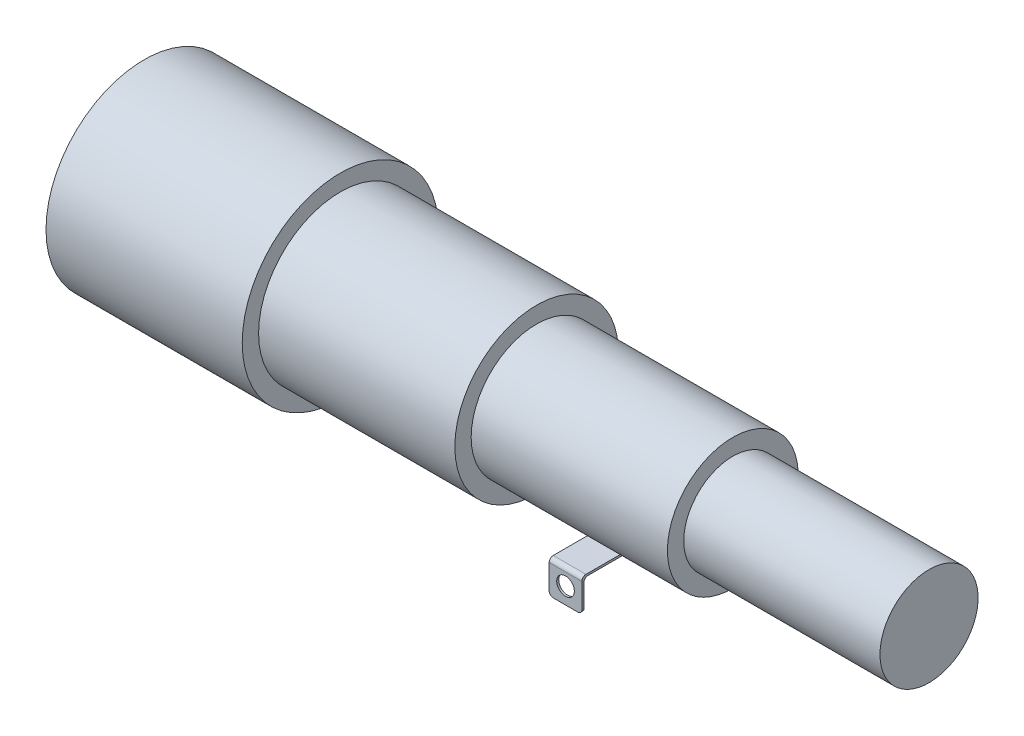
SolidWorks part; units mm, degrees
ref_plane "Front Plane" through (0, 0, 0) normal (0, 0, 1) x (1, 0, 0)
ref_plane "Top Plane" through (0, 0, 0) normal (0, 1, 0) x (1, 0, 0)
ref_plane "Right Plane" through (0, 0, 0) normal (1, 0, 0) x (0, 0, -1)
sketch "Sketch1" plane through (0, 0, 0) normal (1, 0, 0) x (0, 0, -1)
  circle A0 centre (0, 0) radius 152.4
  dimension "D1" = 304.8
extrude "Boss-Extrude1" add sketch "Sketch1" along normal blind 304.8 contours A0
sketch "Sketch2" plane through (304.8, 0, 0) normal (1, 0, 0) x (0, 0, -1)
  circle A0 centre (0, 0) radius 127
  dimension "D1" = 254
extrude "Boss-Extrude2" add sketch "Sketch2" along normal blind 304.8
sketch "Sketch3" plane through (609.6, 0, 0) normal (1, 0, 0) x (0, 0, -1)
  circle A0 centre (0, 0) radius 101.6
  dimension "D1" = 203.2
extrude "Boss-Extrude3" add sketch "Sketch3" along normal blind 304.8
sketch "Sketch4" plane through (914.4, 0, 0) normal (1, 0, 0) x (0, 0, -1)
  circle A0 centre (0, 0) radius 76.2
  dimension "D1" = 152.4
extrude "Boss-Extrude4" add sketch "Sketch4" along normal blind 304.8
sketch "Sketch5" plane through (0, 0, 0) normal (0, 0, 1) x (1, 0, 0)
  line L1 (756.033, 292.8121) -> (756.033, -186.6588) construction
  line L2 (609.6, -101.6) -> (914.4, -101.6) construction
  line L3 (609.6, -101.6) -> (914.4, -101.6) construction
  line L4 (730.633, -101.6) -> (781.433, -101.6)
  line L5 (730.633, -101.6) -> (730.633, -104.775)
  line L6 (730.633, -104.775) -> (781.433, -104.775)
  line L7 (781.433, -104.775) -> (781.433, -101.6)
  point P7 (756.033, -101.6)
  point P11 (756.033, -101.6)
  dimension "D1" = 50.8
  dimension "D2" = 3.175
sketch3d "3DSketch2"
  line L0 (756.033, 292.8121, 0) -> (756.033, -186.6588, 0) construction
sketch "Sketch6" plane through (756.033, 0, 0) normal (-1, 0, 0) x (0, 0, 1)
  line L0 (101.473, -101.6) -> (-101.473, -101.6)
  line L2 (-101.473, -101.6) -> (-101.473, -152.4)
  line L3 (101.473, -101.6) -> (101.473, -152.4)
  line L4 (98.298, -104.775) -> (-98.298, -104.775)
  line L5 (-98.298, -104.775) -> (-98.298, -152.4)
  line L6 (-98.298, -152.4) -> (-101.473, -152.4)
  line L7 (98.298, -104.775) -> (98.298, -152.4)
  line L8 (98.298, -152.4) -> (101.473, -152.4)
  point P4 (0, -101.6)
  dimension "D1" = 202.946
  dimension "D2" = 3.175
  dimension "D3" = 3.175
  dimension "D4" = 3.175
  dimension "D5" = 50.8
extrude "Boss-Extrude6" add sketch "Sketch6" along normal mid plane 50.8 separate body
fillet "Fillet1" radius 6.35 8 edges at (781.433, -152.4, -99.8855) (781.433, -152.4, 99.8855) (730.633, -152.4, -99.8855) (730.633, -152.4, 99.8855) (756.033, -104.775, -98.298) (756.033, -101.6, -101.473) (756.033, -101.6, 101.473) (756.033, -104.775, 98.298)
sketch "Sketch7" plane through (0, 0, 101.473) normal (0, 0, 1) x (1, 0, 0)
  line L0 (756.033, -152.4) -> (756.033, -52.9505) construction
  line L1 (736.983, -152.4) -> (775.083, -152.4) construction
  circle A0 centre (756.033, -127) radius 13.716
  dimension "D2" = 27.432
  dimension "D1" = 25.4
extrude "Cut-Extrude1" cut sketch "Sketch7" against normal through all both and the other way through all
